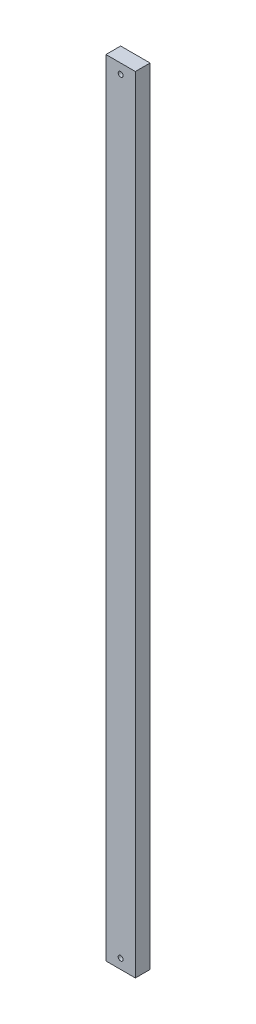
SolidWorks part; units mm, degrees
ref_plane "Front Plane" through (0, 0, 0) normal (0, 0, 1) x (1, 0, 0)
ref_plane "Top Plane" through (0, 0, 0) normal (0, 1, 0) x (1, 0, 0)
ref_plane "Right Plane" through (0, 0, 0) normal (1, 0, 0) x (0, 0, -1)
sketch "Sketch1" plane through (0, 0, 0) normal (0, 1, 0) x (1, 0, 0)
  line L1 (19.05, 9.525) -> (-19.05, 9.525)
  line L2 (19.05, 9.525) -> (19.05, -9.525)
  line L3 (19.05, -9.525) -> (-19.05, -9.525)
  line L4 (-19.05, 9.525) -> (-19.05, -9.525)
  line L5 (19.05, 9.525) -> (-19.05, -9.525) construction
  line L6 (19.05, -9.525) -> (-19.05, 9.525) construction
  point P0 (0, 0)
  dimension "D1" = 19.05
  dimension "D2" = 38.1
extrude "Boss-Extrude1" add sketch "Sketch1" along normal blind 1016
sketch "Sketch2" plane through (0, 0, 9.525) normal (0, 0, 1) x (1, 0, 0)
  line L0 (-19.05, 0) -> (19.05, 0) construction
  line L1 (-19.05, 1016) -> (-19.05, 0) construction
  line L2 (-19.05, 1016) -> (19.05, 1016) construction
  line L3 (19.05, 1016) -> (19.05, 0) construction
  circle A0 centre (0, 12.7) radius 3.175
  circle A1 centre (0, 1003.3) radius 3.175
  dimension "D1" = 6.35
  dimension "D3" = 19.05
  dimension "D4" = 6.35
  dimension "D5" = 12.7
  dimension "D6" = 19.05
  dimension "D2" = 12.7
extrude "Cut-Extrude1" cut sketch "Sketch2" against normal blind 1016
